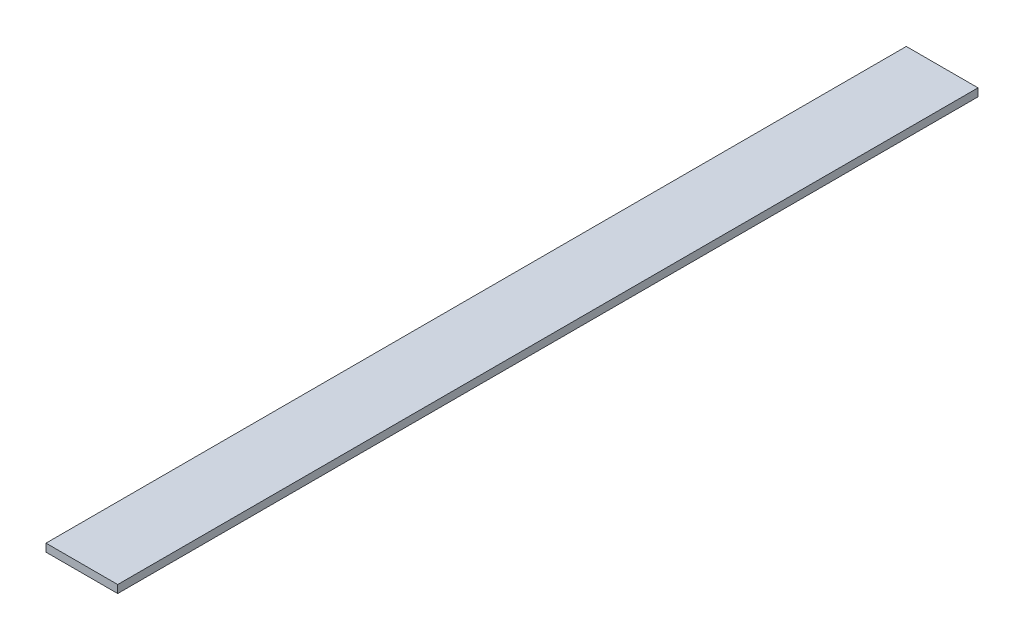
SolidWorks part; units mm, degrees
ref_plane "Front Plane" through (0, 0, 0) normal (0, 0, 1) x (1, 0, 0)
ref_plane "Top Plane" through (0, 0, 0) normal (0, 1, 0) x (1, 0, 0)
ref_plane "Right Plane" through (0, 0, 0) normal (1, 0, 0) x (0, 0, -1)
sketch "Sketch1" plane through (0, 0, 0) normal (0, 0, 1) x (1, 0, 0)
  line L7 (-50.8, -5.5562) -> (50.8, -5.5562)
  line L8 (-50.8, -5.5562) -> (-50.8, 5.5562)
  line L9 (-50.8, 5.5562) -> (50.8, 5.5562)
  line L10 (50.8, -5.5562) -> (50.8, 5.5562)
  line L11 (-50.8, -5.5562) -> (50.8, 5.5562) construction
  line L12 (-50.8, 5.5562) -> (50.8, -5.5562) construction
  point P4 (0, 0)
  point P14 (0, 0)
  dimension "Width" = 101.6
  dimension "Thickness" = 11.1125
sketch "Sketch2" plane through (0, 0, 0) normal (0, 1, 0) x (0, 0, -1)
  line L0 (609.6, 50.8) -> (-609.6, 50.8) construction
  point P0 (-482.6, 50.8)
  point P4 (0, 50.8)
  point P6 (482.6, 50.8)
  dimension "Length" = 1219.2
  dimension "D1" = 127
  dimension "D2" = 127
sketch "Sketch3" plane through (0, 0, 0) normal (0, 0, 1) x (1, 0, 0)
  line L6 (-50.8, 5.5562) -> (50.8, 5.5562)
  line L7 (50.8, 5.5562) -> (50.8, -5.5562)
  line L8 (50.8, -5.5562) -> (-50.8, -5.5562)
  line L9 (-50.8, -5.5562) -> (-50.8, 5.5562)
extrude "Boss-Extrude1" add sketch "Sketch3" along normal mid plane 1219.2
equation "\"D1@Boss-Extrude1\" = \"Length@Sketch2\""
equation "\"D1@Sketch2\"=\"Width@Sketch1\" * 1.25"
equation "\"D2@Sketch2\"=\"D1@Sketch2\""
